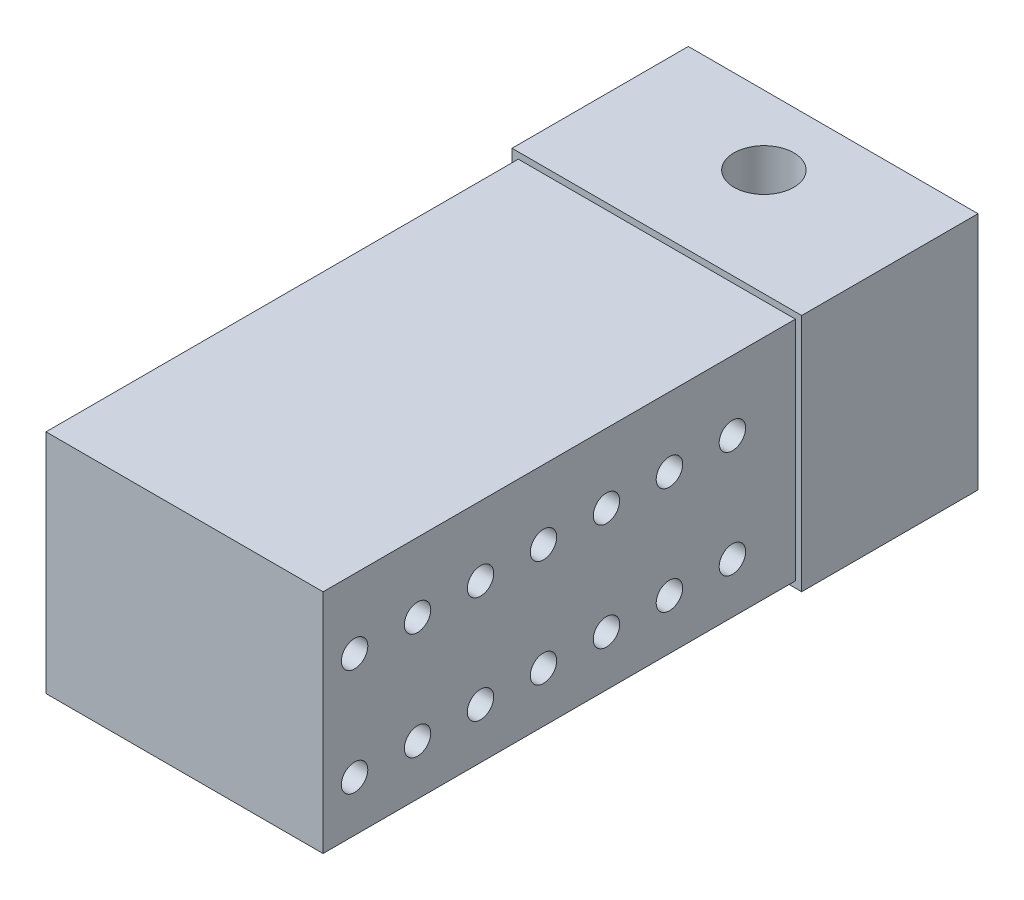
SolidWorks part; units mm, degrees
ref_plane "Front Plane" through (0, 0, 0) normal (0, 0, 1) x (1, 0, 0)
ref_plane "Top Plane" through (0, 0, 0) normal (0, 1, 0) x (1, 0, 0)
ref_plane "Right Plane" through (0, 0, 0) normal (1, 0, 0) x (0, 0, -1)
sketch "Sketch1" plane through (0, 0, 0) normal (0, 0, 1) x (1, 0, 0)
  line L0 (-4.064, -3.048) -> (4.064, -3.048)
  line L1 (-5.842, 4.826) -> (5.842, 4.826)
  line L2 (-5.842, 4.826) -> (-5.842, -4.826)
  line L3 (-5.842, -4.826) -> (5.842, -4.826)
  line L4 (5.842, 4.826) -> (5.842, -4.826)
  line L5 (-5.842, 4.826) -> (5.842, -4.826) construction
  line L6 (-5.842, -4.826) -> (5.842, 4.826) construction
  line L7 (4.064, -3.048) -> (4.064, -0.381)
  line L8 (4.064, -0.381) -> (3.048, -0.381)
  line L9 (3.048, -0.381) -> (3.048, 3.048)
  line L10 (3.048, 3.048) -> (-3.048, 3.048)
  line L11 (-3.048, 3.048) -> (-3.048, -0.381)
  line L12 (-3.048, -0.381) -> (-4.064, -0.381)
  line L13 (-4.064, -0.381) -> (-4.064, -3.048)
  point P5 (0, 3.048)
  point P7 (0, 0)
  dimension "D1" = 11.684
  dimension "D2" = 9.652
  dimension "D3" = 1.778
  dimension "D4" = 6.096
  dimension "D5" = 3.429
  dimension "D6" = 6.096
  dimension "D7" = 8.128
extrude "Boss-Extrude1" add sketch "Sketch1" along normal blind 7.112
sketch "Sketch2" plane through (0, 4.826, 0) normal (0, 1, 0) x (1, 0, 0)
  line L1 (5.842, 0) -> (-5.842, 0) construction
  circle A0 centre (0, -2.794) radius 1.2065
  dimension "D1" = 2.413
  dimension "D2" = 2.794
extrude "Cut-Extrude1" cut sketch "Sketch2" against normal through all both and the other way through all
sketch "Sketch3" plane through (0, 0, 7.112) normal (0, 0, 1) x (1, 0, 0)
  line L1 (-5.842, 4.826) -> (5.842, 4.826)
  line L2 (-5.842, 4.826) -> (-5.842, -4.826)
  line L3 (-5.842, -4.826) -> (5.842, -4.826)
  line L4 (5.842, 4.826) -> (5.842, -4.826)
sketch "Sketch7" plane through (0, 0, 7.112) normal (0, 0, 1) x (1, 0, 0)
  line L14 (-5.588, -4.572) -> (5.588, -4.572)
  line L15 (5.588, -4.572) -> (5.588, 4.572)
  line L16 (5.588, 4.572) -> (-5.588, 4.572)
  line L17 (-5.588, 4.572) -> (-5.588, -4.572)
  line L18 (-5.588, -4.572) -> (5.588, -4.572)
  line L19 (5.588, -4.572) -> (5.588, 4.572)
  line L20 (5.588, 4.572) -> (-5.588, 4.572)
  line L21 (-5.588, 4.572) -> (-5.588, -4.572)
  dimension "D1" = 0.254
extrude "Boss-Extrude3" add sketch "Sketch7" along normal blind 19.05
sketch "Sketch9" plane through (5.588, 0, 0) normal (1, 0, 0) x (0, 0, -1)
  line L0 (-26.162, -4.572) -> (-7.112, -4.572) construction
  line L1 (-7.112, 4.826) -> (-7.112, -4.826) construction
  line L2 (-9.652, -2.54) -> (-12.192, -2.54) construction
  line L3 (-9.652, -2.54) -> (-9.652, 1.778) construction
  circle A0 centre (-9.652, -2.54) radius 0.5334
  circle A1 centre (-12.192, -2.54) radius 0.5334
  circle A2 centre (-14.732, -2.54) radius 0.5334
  circle A3 centre (-17.272, -2.54) radius 0.5334
  circle A4 centre (-19.812, -2.54) radius 0.5334
  circle A5 centre (-22.352, -2.54) radius 0.5334
  circle A6 centre (-24.892, -2.54) radius 0.5334
  circle A7 centre (-12.192, 1.778) radius 0.5334
  circle A8 centre (-14.732, 1.778) radius 0.5334
  circle A9 centre (-17.272, 1.778) radius 0.5334
  circle A10 centre (-19.812, 1.778) radius 0.5334
  circle A11 centre (-22.352, 1.778) radius 0.5334
  circle A12 centre (-24.892, 1.778) radius 0.5334
  circle A13 centre (-9.652, 1.778) radius 0.5334
  point P6 (0, 0)
  dimension "D1" = 1.0668
  dimension "D2" = 2.032
  dimension "D3" = 2.54
  dimension "D7" = 2.54
  dimension "D8" = 4.318
  dimension "D4" = 7
  dimension "D5" = 2
extrude "Cut-Extrude2" cut sketch "Sketch9" against normal through all
